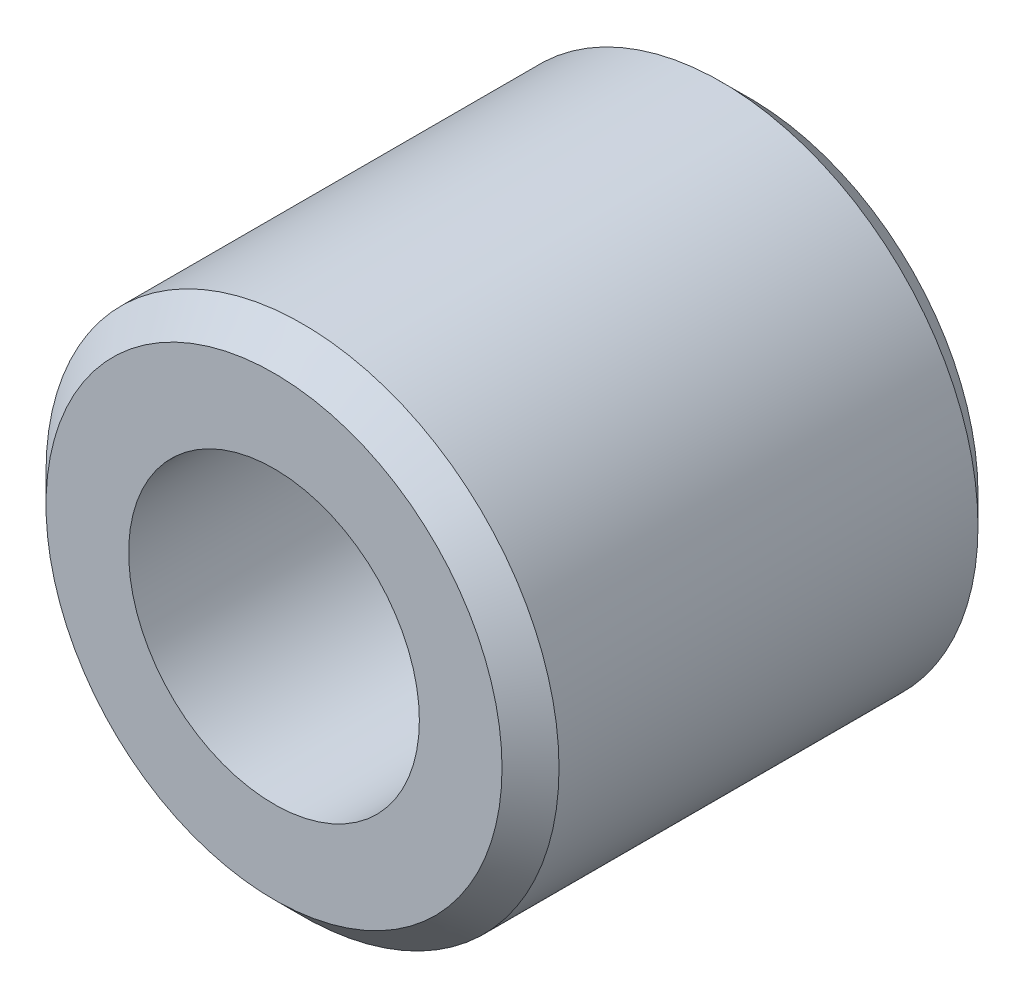
SolidWorks part; units mm, degrees
ref_plane "Front Plane" through (0, 0, 0) normal (0, 0, 1) x (1, 0, 0)
ref_plane "Top Plane" through (0, 0, 0) normal (0, 1, 0) x (1, 0, 0)
ref_plane "Right Plane" through (0, 0, 0) normal (1, 0, 0) x (0, 0, -1)
sketch "Sketch1" plane through (0, 0, 0) normal (0, 0, 1) x (1, 0, 0)
  circle A0 centre (0, 0) radius 4.5
  dimension "D1" = 9
extrude "Boss-Extrude1" add sketch "Sketch1" along normal blind 8.35
sketch "Sketch2" plane through (0, 0, 0) normal (0, 0, 1) x (1, 0, 0)
  circle A0 centre (0, 0) radius 2.55
  dimension "D1" = 5.1
extrude "Cut-Extrude1" cut sketch "Sketch2" along normal through all
chamfer "Chamfer1" distance 0.5 angle 45 2 edges at (4.5, 0, 0) (4.5, 0, 8.35)
